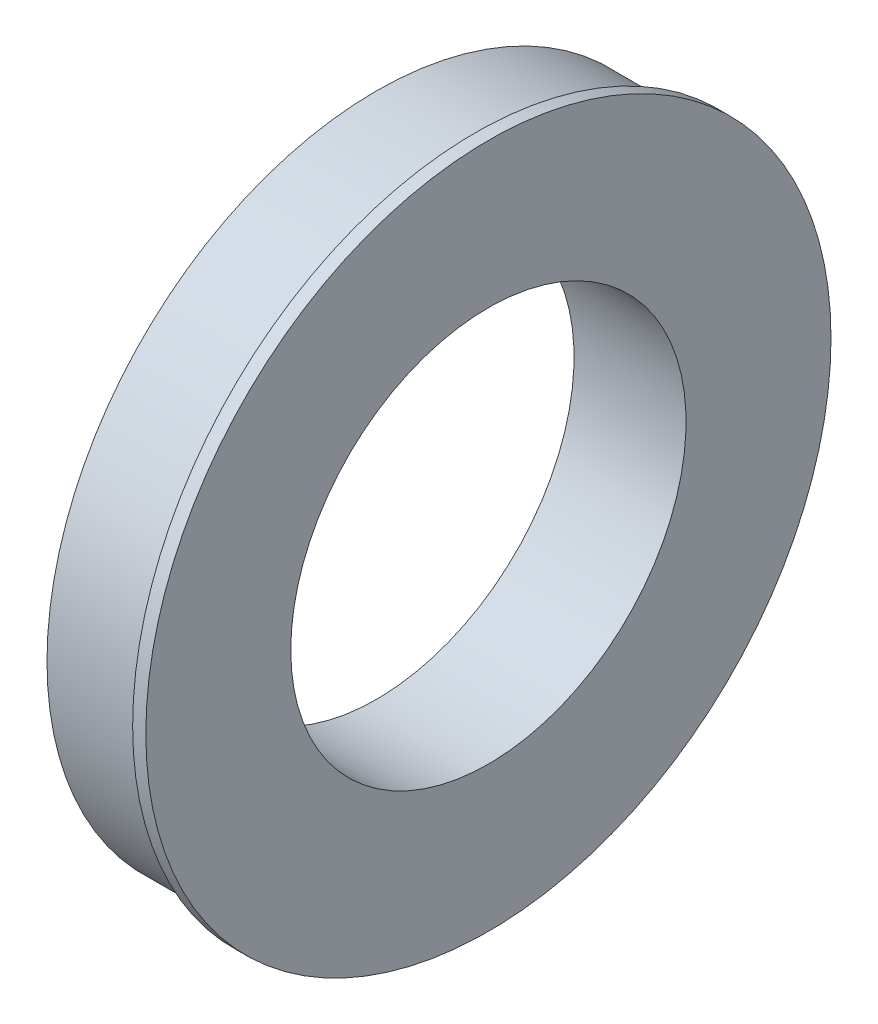
SolidWorks part; units mm, degrees
material "AISI 1045 Steel, cold drawn"
ref_plane "Front Plane" through (0, 0, 0) normal (0, 0, 1) x (1, 0, 0)
ref_plane "Top Plane" through (0, 0, 0) normal (0, 1, 0) x (1, 0, 0)
ref_plane "Right Plane" through (0, 0, 0) normal (1, 0, 0) x (0, 0, -1)
sketch "Sketch1" plane through (0, 0, 0) normal (1, 0, 0) x (0, 0, -1)
  circle A0 centre (0, 0) radius 38.1
  circle A1 centre (0, 0) radius 63.5
  dimension "D1" = 127
  dimension "D2" = 76.2
extrude "Boss-Extrude1" add sketch "Sketch1" along normal blind 19.05
sketch "Sketch2" plane through (19.05, 0, 0) normal (1, 0, 0) x (0, 0, -1)
  circle A1 centre (0, 0) radius 38.1 construction
  circle A2 centre (0, 0) radius 66.04
  circle A3 centre (0, 0) radius 66.04
  circle A4 centre (0, 0) radius 38.1
  dimension "D1" = 2.54
extrude "Boss-Extrude2" add sketch "Sketch2" along normal blind 2.54
